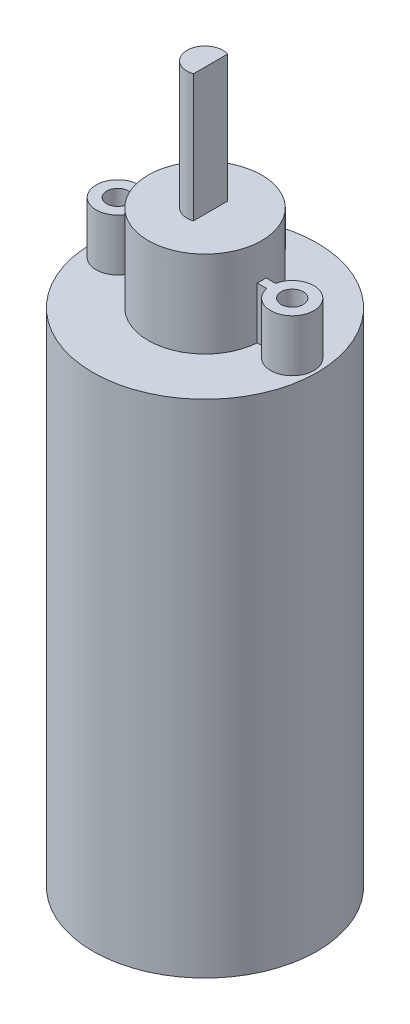
SolidWorks part; units mm, degrees
ref_plane "Front Plane" through (0, 0, 0) normal (0, 0, 1) x (1, 0, 0)
ref_plane "Top Plane" through (0, 0, 0) normal (0, 1, 0) x (1, 0, 0)
ref_plane "Right Plane" through (0, 0, 0) normal (1, 0, 0) x (0, 0, -1)
sketch "Sketch1" plane through (0, 0, 0) normal (0, 1, 0) x (1, 0, 0)
  circle A0 centre (0, 0) radius 10.287
  dimension "D1" = 20.574
extrude "Boss-Extrude1" add sketch "Sketch1" along normal blind 45.974
sketch "Sketch2" plane through (0, 45.974, 0) normal (0, 1, 0) x (1, 0, 0)
  circle A0 centre (0, 0) radius 5.207
  dimension "D1" = 10.414
extrude "Boss-Extrude2" add sketch "Sketch2" along normal blind 7.9375
sketch "Sketch3" plane through (0, 53.9115, 0) normal (0, 1, 0) x (1, 0, 0)
  circle A0 centre (0, 0) radius 1.651
  dimension "D1" = 3.302
extrude "Boss-Extrude3" add sketch "Sketch3" along normal blind 11.684
sketch "Sketch4" plane through (0, 45.974, 0) normal (0, 1, 0) x (1, 0, 0)
  line L0 (-8.001, 0) -> (8.001, 0) construction
  line L2 (-6.4626, 0.405) -> (6.4948, 0.405)
  line L3 (-6.4626, 0.405) -> (-6.4626, -0.405)
  line L4 (-6.4626, -0.405) -> (6.4948, -0.405)
  line L5 (6.4948, 0.405) -> (6.4948, -0.405)
  circle A1 centre (-8.001, 0) radius 1.9844
  circle A2 centre (8.001, 0) radius 1.9844
  circle A3 centre (-8.001, 0) radius 1.016
  circle A4 centre (8.001, 0) radius 1.016
  point P2 (0, 0)
  point P14 (-6.4626, 0)
  dimension "D2" = 3.9688
  dimension "D3" = 2.032
  dimension "D1" = 16.002
  dimension "D4" = 0.81
  dimension "D5" = 12.9574
  dimension "D6" = 6.4626
extrude "Boss-Extrude5" add sketch "Sketch4" along normal blind 4.7625
sketch "Sketch5" plane through (0, 65.5955, 0) normal (0, 1, 0) x (1, 0, 0)
  line L0 (0.508, 1.5709) -> (0.508, -1.5709)
  circle A0 centre (0, 0) radius 1.651 construction
  circle A2 centre (0, 0) radius 1.651
  circle M2 centre (0, 0) radius 1.651
  dimension "D1" = 0.508
extrude "Cut-Extrude1" cut sketch "Sketch5" against normal up to surface (11.684 mm away) contours L0 M2
equation "\"motor diamiter\"= 20.65mm"
equation "\"little diamiter\"= 10.3mm"
equation "\"shaft diamiter\"= 3.34mm"
equation "\"hole spacing\"= 16mm"
equation "\"hole size\"= 2mm'probobly"
equation "\"hole stickout\"= 3 / 16in"
equation "\"small diamiter length\"= 5 / 16in"
equation "\"Outer Hole size\"= 5 / 32"
equation "\"length\"= 46.05mm"
equation "\"D1@Sketch1\"=\"motor diamiter\""
equation "\"D1@Boss-Extrude1\"=\"length\""
equation "\"D1@Sketch2\"=\"little diamiter\""
equation "\"D1@Boss-Extrude2\"=\"small diamiter length\""
equation "\"D1@Sketch3\"=\"shaft diamiter\""
equation "\"shaft length\"= 11.7mm"
equation "\"D1@Boss-Extrude3\"=\"shaft length\""
equation "\"D1@Sketch4\"=\"hole spacing\""
equation "\"D2@Sketch4\"=\"Outer Hole size\""
equation "\"D3@Sketch4\"=\"hole size\""
equation "\"D1@Boss-Extrude5\"=\"hole stickout\""
